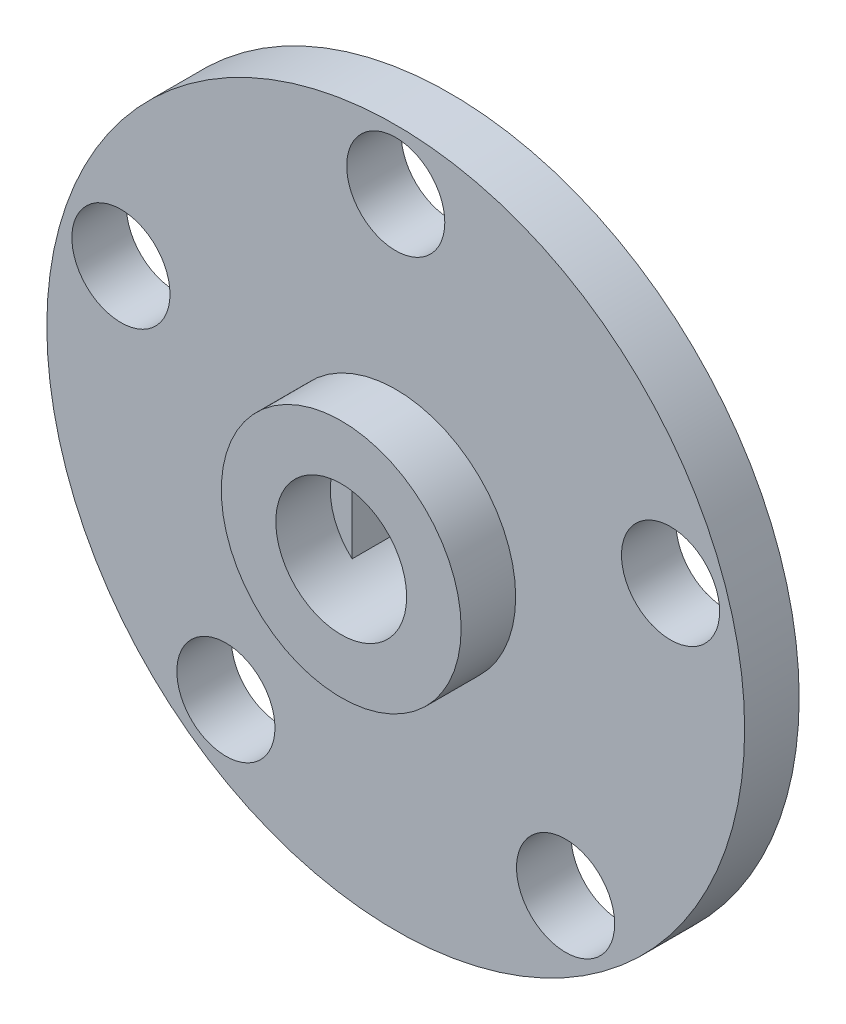
SolidWorks part; units mm, degrees
ref_plane "Front Plane" through (0, 0, 0) normal (0, 0, 1) x (1, 0, 0)
ref_plane "Top Plane" through (0, 0, 0) normal (0, 1, 0) x (1, 0, 0)
ref_plane "Right Plane" through (0, 0, 0) normal (1, 0, 0) x (0, 0, -1)
sketch "Sketch1" plane through (0, 0, 0) normal (0, 1, 0) x (1, 0, 0)
  line L0 (0, 0) -> (0, 10) construction
  line L1 (4, 10) -> (32, 10)
  line L3 (6, 0) -> (6, 5)
  line L4 (32, 10) -> (32, 0)
  line L8 (6, 0) -> (6, 10) construction
  line L9 (32, 0) -> (6, 0)
  line L12 (4, 5) -> (6, 5)
  line L13 (4, 10) -> (4, 5)
  dimension "D5" = 10
  dimension "D1" = 32
  dimension "D2" = 4
  dimension "D3" = 6
revolve "Revolve1" add sketch "Sketch1" angle 360 about L0
sketch "Sketch2" plane through (0, 0, -10) normal (0, 0, -1) x (-1, 0, 0)
  line L1 (-4, 4.4721) -> (-4, -4.4721)
  line L2 (4, 4.4721) -> (4, -4.4721)
  arc A0 (-4, -4.4721) -> (4, -4.4721) centre (0, 0) ccw
  arc A1 (4, 4.4721) -> (-4, 4.4721) centre (0, 0) ccw
  dimension "D3" = 12
extrude "Cut-Extrude1" cut sketch "Sketch2" against normal blind 5
sketch "Sketch3" plane through (0, 0, 0) normal (0, 0, 1) x (1, 0, 0)
  circle A0 centre (0, 0) radius 11
  circle A1 centre (0, 0) radius 32
  dimension "D1" = 22
extrude "Cut-Extrude2" cut sketch "Sketch3" against normal blind 5
sketch "Sketch4" plane through (0, 0, -5) normal (0, 0, 1) x (1, 0, 0)
  circle A4 centre (0, 26.5) radius 4.5
  circle A5 centre (25.203, 8.189) radius 4.5
  circle A6 centre (15.5763, -21.439) radius 4.5
  circle A7 centre (-15.5763, -21.439) radius 4.5
  circle A8 centre (-25.203, 8.189) radius 4.5
  point P17 (0, 0)
  dimension "D1" = 5
extrude "Cut-Extrude3" cut sketch "Sketch4" against normal blind 5
